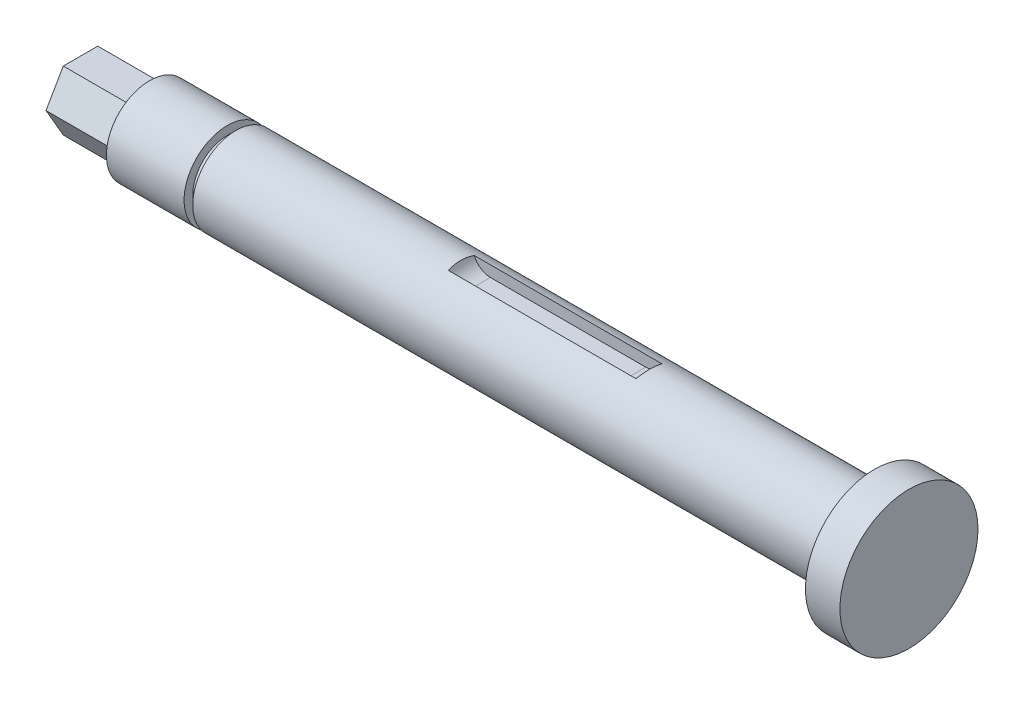
SolidWorks part; units mm, degrees
material "Chrome Stainless Steel"
ref_plane "Front Plane" through (0, 0, 0) normal (0, 0, 1) x (1, 0, 0)
ref_plane "Top Plane" through (0, 0, 0) normal (0, 1, 0) x (1, 0, 0)
ref_plane "Right Plane" through (0, 0, 0) normal (1, 0, 0) x (0, 0, -1)
sketch "Sketch1" plane through (0, 0, 0) normal (0, 0, 1) x (1, 0, 0)
  line L0 (0, 0) -> (-20.2261, 0) construction
  line L1 (0, 0) -> (0, 6.35)
  line L2 (0, 0) -> (152.4, 0)
  line L3 (152.4, 0) -> (152.4, 12.7)
  line L4 (152.4, 12.7) -> (146.05, 12.7)
  line L5 (146.05, 12.7) -> (146.05, 7.9375)
  line L6 (146.05, 7.9375) -> (28.575, 7.9375)
  line L7 (0, 6.35) -> (12.7, 6.35)
  line L8 (12.7, 6.35) -> (12.7, 7.9375)
  line L9 (12.7, 7.9375) -> (26.9875, 7.9375)
  line L10 (26.9875, 7.9375) -> (26.9875, 6.35)
  line L11 (26.9875, 6.35) -> (28.575, 6.35)
  line L12 (28.575, 6.35) -> (28.575, 7.9375)
  dimension "D1" = 6.35
  dimension "D2" = 12.7
  dimension "D3" = 15.875
  dimension "D4" = 25.4
  dimension "D5" = 1.5875
  dimension "D6" = 1.5875
  dimension "D7" = 12.7
  dimension "D8" = 133.35
  dimension "D9" = 117.475
revolve "Base" add sketch "Sketch1" angle 360 about L0
sketch "Sketch2" plane through (0, 0, 0) normal (0, 0, 1) x (1, 0, 0)
  line L0 (69.85, 14.2875) -> (69.85, 8.7249)
  line L1 (73.025, 5.5499) -> (101.6, 5.5499)
  line L2 (104.775, 8.7249) -> (104.775, 14.2875)
  line L3 (104.775, 14.2875) -> (69.85, 14.2875)
  line L4 (146.05, 7.9375) -> (28.575, 7.9375) construction
  line L5 (0, 6.35) -> (0, -6.35) construction
  arc A0 (69.85, 8.7249) -> (73.025, 5.5499) centre (73.025, 8.7249) ccw
  arc A1 (101.6, 5.5499) -> (104.775, 8.7249) centre (101.6, 8.7249) ccw
  dimension "D4" = 3.175
  dimension "D1" = 34.925
  dimension "D2" = 2.3876
  dimension "D3" = 69.85
  dimension "D5" = 6.35
extrude "Keyway" cut sketch "Sketch2" against normal mid plane 4.7625
sketch "Sketch3" plane through (0, 0, 0) normal (-1, 0, 0) x (0, 0, 1)
  line L1 (3.175, 5.4993) -> (-3.175, 5.4993)
  line L2 (-3.175, 5.4993) -> (-6.35, 0)
  line L3 (-6.35, 0) -> (-3.175, -5.4993)
  line L4 (-3.175, -5.4993) -> (3.175, -5.4993)
  line L5 (3.175, -5.4993) -> (6.35, 0)
  line L6 (6.35, 0) -> (3.175, 5.4993)
  circle A0 centre (0, 0) radius 6.35 construction
  circle A1 centre (0, 0) radius 6.35 construction
extrude "Cut-Extrude2" cut sketch "Sketch3" against normal up to surface (12.7 mm away) flip side to cut up to face at (12.7, 0, -6.35)
